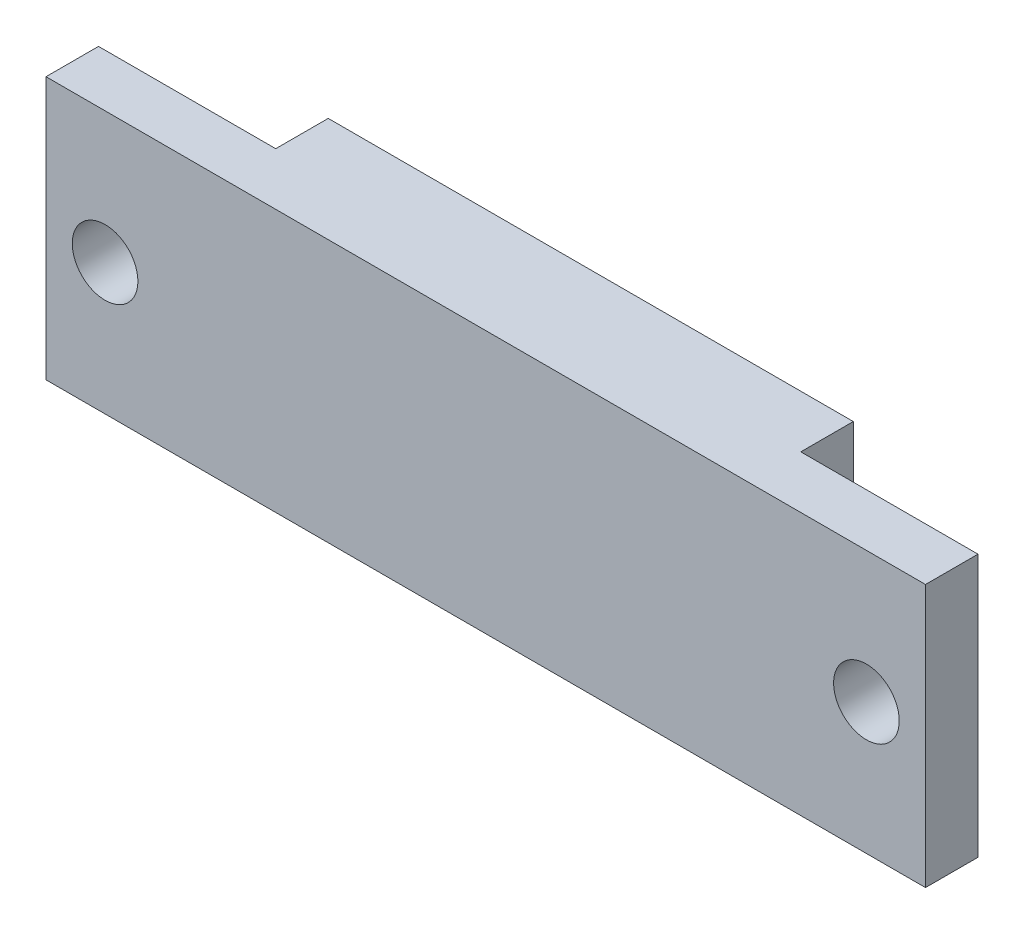
SolidWorks part; units mm, degrees
ref_plane "Front Plane" through (0, 0, 0) normal (0, 0, 1) x (1, 0, 0)
ref_plane "Top Plane" through (0, 0, 0) normal (0, 1, 0) x (1, 0, 0)
ref_plane "Right Plane" through (0, 0, 0) normal (1, 0, 0) x (0, 0, -1)
sketch "Sketch1" plane through (0, 0, 0) normal (0, 1, 0) x (1, 0, 0)
  line L0 (67.945, 0) -> (85.09, 0)
  line L1 (0, 0) -> (17.145, 0)
  line L2 (0, 0) -> (0, -5.08)
  line L3 (0, -5.08) -> (85.09, -5.08)
  line L4 (85.09, 0) -> (85.09, -5.08)
  line L6 (17.145, 0) -> (17.145, 5.08)
  line L7 (17.145, 5.08) -> (67.945, 5.08)
  line L8 (67.945, 0) -> (67.945, 5.08)
  point P9 (52.6087, 3.4368)
  dimension "D1" = 50.8
  dimension "D2" = 5.08
  dimension "D3" = 85.09
  dimension "D4" = 5.08
extrude "Boss-Extrude1" add sketch "Sketch1" along normal blind 25.4
hole_wizard "1/4 (0.25) Diameter Hole1" positions "Sketch2" profile "Sketch3" hole size "1/4" standard "ANSI Inch" end condition through all
sketch "Sketch2" plane through (0, 0, 5.08) normal (0, 0, 1) x (1, 0, 0)
  line L2 (42.545, 0) -> (42.545, 25.4) construction
  line L3 (0, 0) -> (85.09, 0) construction
  line L4 (0, 25.4) -> (85.09, 25.4) construction
  line L6 (5.715, 12.7) -> (79.375, 12.7) construction
  point P0 (5.715, 12.7)
  point P2 (79.375, 12.7)
  point P25 (42.545, 12.7)
  point P26 (42.545, 12.7)
  dimension "D1" = 73.66
sketch "Sketch3" plane through (5.715, 12.7, 5.08) normal (1, 0, 0) x (0, -1, 0)
  line L0 (0, 0) -> (0, 10.16)
  line L1 (0, 10.16) -> (3.175, 10.16)
  line L2 (3.175, 10.16) -> (3.175, 0)
  line L5 (3.175, 0) -> (0, 0)
  line L11 (0, -6.35) -> (0, 107.95) construction
  dimension "Thru Hole Dia." = 6.35
  dimension "Thru Hole Depth" = 10.16
